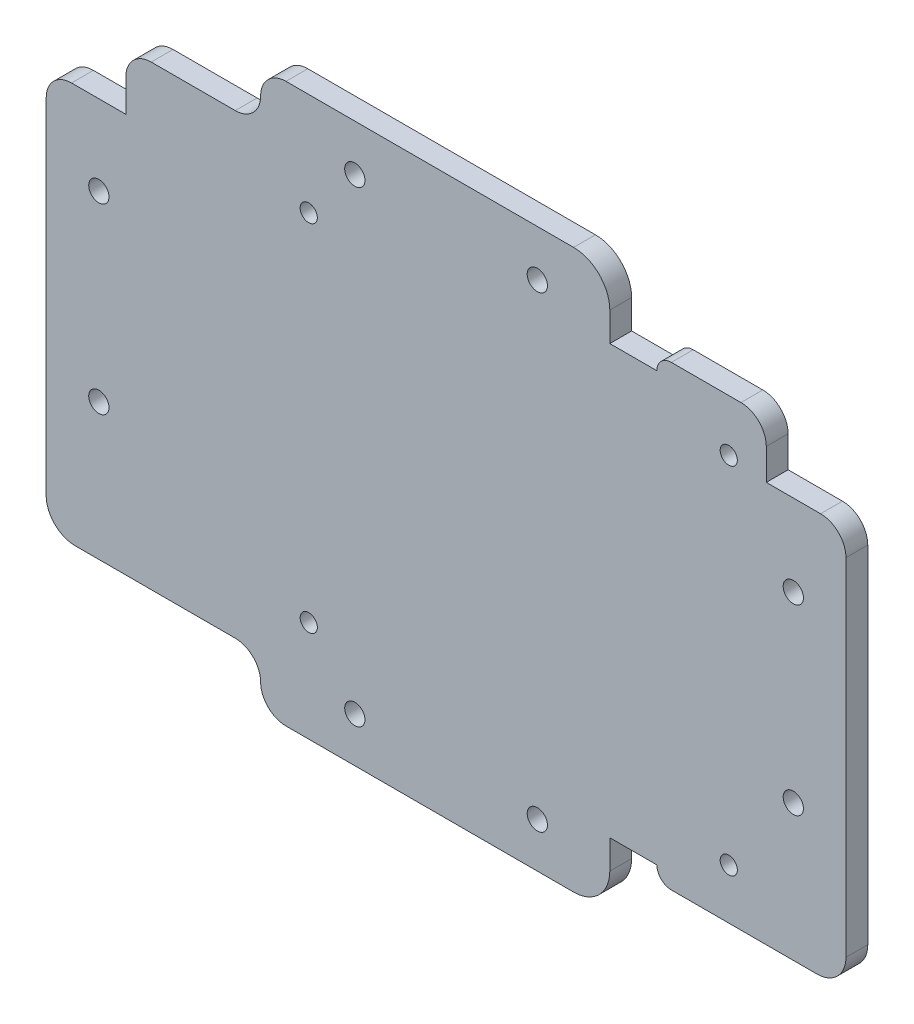
SolidWorks part; units mm, degrees
ref_plane "Alzado" through (0, 0, 0) normal (0, 0, 1) x (1, 0, 0)
ref_plane "Planta" through (0, 0, 0) normal (0, 1, 0) x (1, 0, 0)
ref_plane "Vista lateral" through (0, 0, 0) normal (1, 0, 0) x (0, 0, -1)
sketch "Croquis1" plane through (0, 0, 0) normal (0, 0, 1) x (1, 0, 0)
  line L0 (73.906, 79.342) -> (73.906, 31.8013)
  line L1 (-35.9316, 79.142) -> (-35.9316, 31.6013)
  line L2 (-31.9533, 27.823) -> (-9.964, 27.823)
  line L3 (49.9277, 27.823) -> (69.9277, 27.823)
  line L4 (59.4847, 90.5796) -> (49.9277, 90.5796)
  line L5 (-32.4506, 82.623) -> (-24.9913, 82.623)
  line L6 (-24.9913, 82.623) -> (-24.9913, 87.0986)
  line L7 (70.425, 82.823) -> (62.9657, 82.823)
  line L8 (62.9657, 82.823) -> (62.9657, 87.0986)
  line L9 (-9.964, 90.5796) -> (-21.5102, 90.5796)
  line L10 (-3.002, 97.5417) -> (36.5009, 97.5417)
  line L11 (41.4738, 92.5688) -> (41.4738, 88.5905)
  line L12 (-3.002, 20.861) -> (36.5009, 20.861)
  line L13 (41.4738, 25.8339) -> (41.4738, 29.8122)
  line L14 (41.4738, 29.8122) -> (47.9385, 29.8122)
  line L15 (47.9385, 88.5905) -> (41.4738, 88.5905)
  arc A0 (-35.9316, 31.6013) -> (-31.9533, 27.823) centre (-31.9583, 31.8013) ccw
  arc A1 (69.9277, 27.823) -> (73.906, 31.8013) centre (69.9277, 31.8013) ccw
  circle A2 centre (-28.7026, 46.5697) radius 1.3924
  circle A3 centre (-28.7026, 71.633) radius 1.3924
  circle A4 centre (66.6771, 46.5697) radius 1.3924
  circle A5 centre (66.6771, 71.633) radius 1.3924
  circle A6 centre (6.4556, 91.1764) radius 1.3924
  circle A7 centre (31.5189, 91.1764) radius 1.3924
  circle A8 centre (6.4556, 27.0263) radius 1.3924
  circle A9 centre (31.5189, 27.0263) radius 1.3924
  arc A10 (-6.483, 24.342) -> (-9.964, 27.823) centre (-9.964, 24.342) ccw
  arc A11 (-6.483, 24.342) -> (-3.002, 20.861) centre (-3.002, 24.342) ccw
  arc A12 (-3.002, 97.5417) -> (-6.483, 94.0607) centre (-3.002, 94.0607) ccw
  arc A13 (-9.964, 90.5796) -> (-6.483, 94.0607) centre (-9.964, 94.0607) ccw
  arc A14 (62.9657, 87.0986) -> (59.4847, 90.5796) centre (59.4847, 87.0986) ccw
  arc A15 (73.906, 79.342) -> (70.425, 82.823) centre (70.425, 79.342) ccw
  arc A16 (-21.5102, 90.5796) -> (-24.9913, 87.0986) centre (-21.5102, 87.0986) ccw
  arc A17 (-32.4506, 82.623) -> (-35.9316, 79.142) centre (-32.4506, 79.142) ccw
  arc A18 (47.9385, 29.8122) -> (49.9277, 27.823) centre (49.9277, 29.8122) ccw
  arc A19 (49.9277, 90.5796) -> (47.9385, 88.5905) centre (49.9277, 88.5905) ccw
  arc A20 (41.4738, 92.5688) -> (36.5009, 97.5417) centre (36.5009, 92.5688) ccw
  arc A21 (36.5009, 20.861) -> (41.4738, 25.8339) centre (36.5009, 25.8339) ccw
  circle A22 centre (0.1255, 83.4684) radius 1.1139
  circle A23 centre (0.1255, 34.7343) radius 1.1139
  circle A24 centre (57.8108, 34.7343) radius 1.1139
  circle A25 centre (57.8108, 83.4684) radius 1.1139
  dimension "D1" = 54.8
extrude "Saliente-Extruir1" add sketch "Croquis1" along normal blind 3
sketch "Croquis8" plane through (0, 0, 3) normal (0, 0, 1) x (1, 0, 0)
  circle A0 centre (0.1255, 34.7343) radius 1.18
  circle A1 centre (57.8108, 34.7343) radius 1.18
  circle A2 centre (0.1255, 83.4684) radius 1.18
  circle A3 centre (57.8108, 83.4684) radius 1.18
  dimension "D1" = 2.36
  dimension "D2" = 2.36
  dimension "D3" = 2.36
  dimension "D4" = 2.36
extrude "Cortar-Extruir1" cut sketch "Croquis8" against normal blind 10
